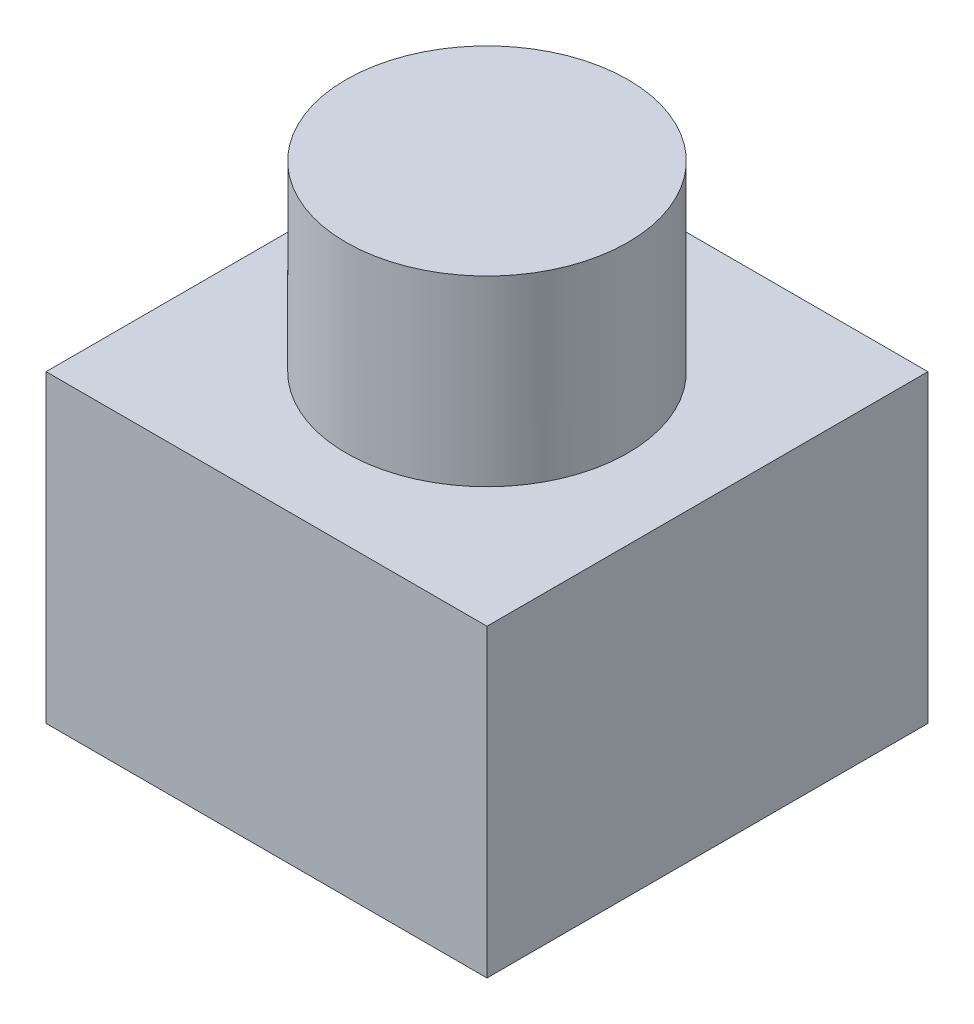
SolidWorks part; units mm, degrees
ref_plane "Front Plane" through (0, 0, 0) normal (0, 0, 1) x (1, 0, 0)
ref_plane "Top Plane" through (0, 0, 0) normal (0, 1, 0) x (1, 0, 0)
ref_plane "Right Plane" through (0, 0, 0) normal (1, 0, 0) x (0, 0, -1)
sketch "Sketch1" plane through (0, 0, 0) normal (0, 1, 0) x (1, 0, 0)
  line L1 (27.5, 27.5) -> (-27.5, 27.5)
  line L2 (27.5, 27.5) -> (27.5, -27.5)
  line L3 (27.5, -27.5) -> (-27.5, -27.5)
  line L4 (-27.5, 27.5) -> (-27.5, -27.5)
  line L5 (27.5, 27.5) -> (-27.5, -27.5) construction
  line L6 (27.5, -27.5) -> (-27.5, 27.5) construction
  point P0 (0, 0)
  dimension "D1" = 55
extrude "Boss-Extrude1" add sketch "Sketch1" along normal blind 38
sketch "Sketch2" plane through (0, 38, 0) normal (0, 1, 0) x (1, 0, 0)
  circle A0 centre (0, 0) radius 17.5838
extrude "Boss-Extrude2" add sketch "Sketch2" along normal blind 22.76
